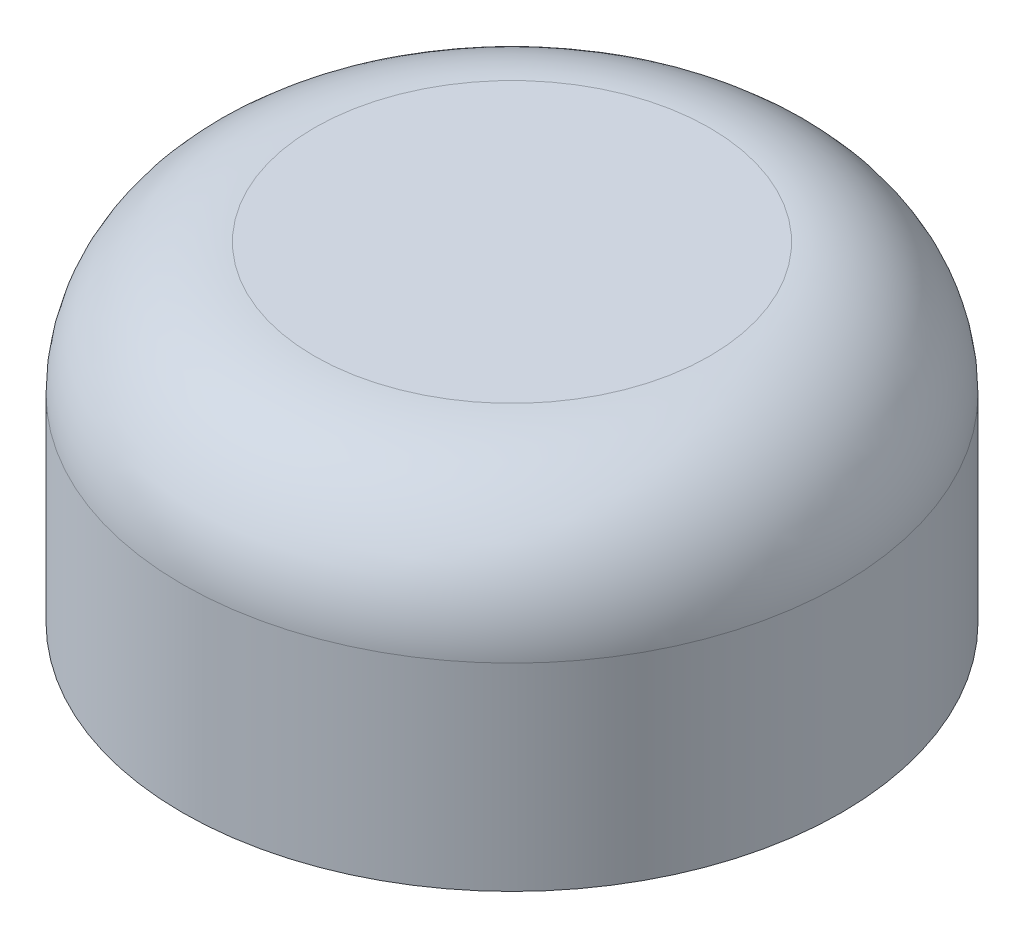
SolidWorks part; units mm, degrees
ref_plane "Front Plane" through (0, 0, 0) normal (0, 0, 1) x (1, 0, 0)
ref_plane "Top Plane" through (0, 0, 0) normal (0, 1, 0) x (1, 0, 0)
ref_plane "Right Plane" through (0, 0, 0) normal (1, 0, 0) x (0, 0, -1)
sketch "Sketch1" plane through (0, 0, 0) normal (0, 0, 1) x (1, 0, 0)
  line L0 (53.9552, 24.2157) -> (53.9552, 23.7157) construction
  line L1 (53.9552, 23.7157) -> (54.4552, 23.7157)
  line L2 (53.9552, 24.2157) -> (53.9552, 23.7157)
  line L3 (53.9552, 24.2157) -> (54.2552, 24.2157)
  line L4 (54.4552, 23.7157) -> (54.4552, 24.0157)
  line L5 (-54.6791, -24.3153) -> (54.4552, 24.2157) construction
  line L6 (-55.0492, -23.9744) -> (54.4552, 23.7157) construction
  arc A0 (54.4552, 24.0157) -> (54.2552, 24.2157) centre (54.2552, 24.0157) ccw
  point P0 (0, 0)
  dimension "D1" = 0.2
  dimension "D2" = 0.5
  dimension "D3" = 0.3
revolve "Revolve1" add sketch "Sketch1" angle 360 about L2
